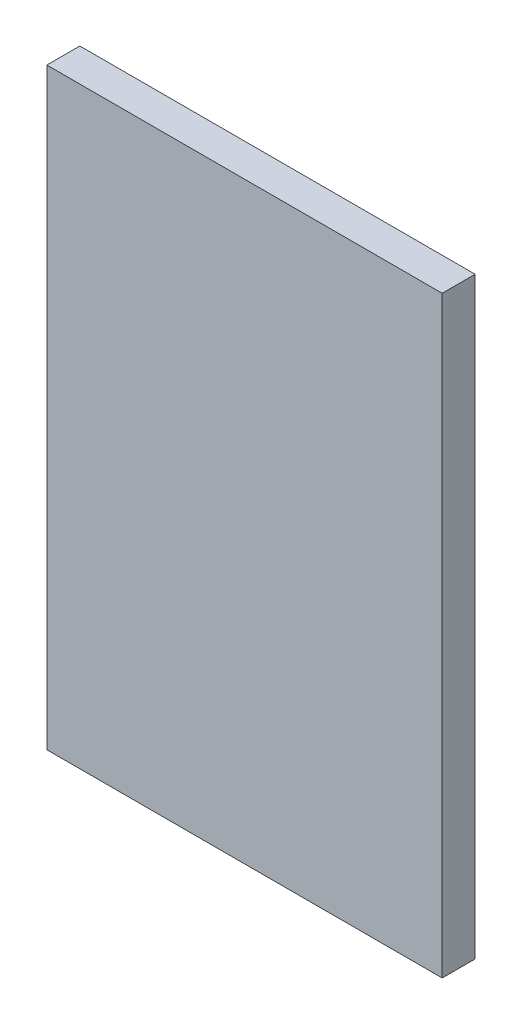
SolidWorks part; units mm, degrees
ref_plane "前视基准面" through (0, 0, 0) normal (0, 0, 1) x (1, 0, 0)
ref_plane "上视基准面" through (0, 0, 0) normal (0, 1, 0) x (1, 0, 0)
ref_plane "右视基准面" through (0, 0, 0) normal (1, 0, 0) x (0, 0, -1)
sketch "草图1" plane through (0, 0, 0) normal (0, 0, 1) x (1, 0, 0)
  line L1 (-6, -9) -> (6, -9)
  line L2 (-6, -9) -> (-6, 9)
  line L3 (-6, 9) -> (6, 9)
  line L4 (6, -9) -> (6, 9)
  line L5 (-6, -9) -> (6, 9) construction
  line L6 (-6, 9) -> (6, -9) construction
  point P0 (0, 0)
  dimension "D1" = 12
  dimension "D2" = 18
extrude "凸台-拉伸1" add sketch "草图1" along normal blind 1
